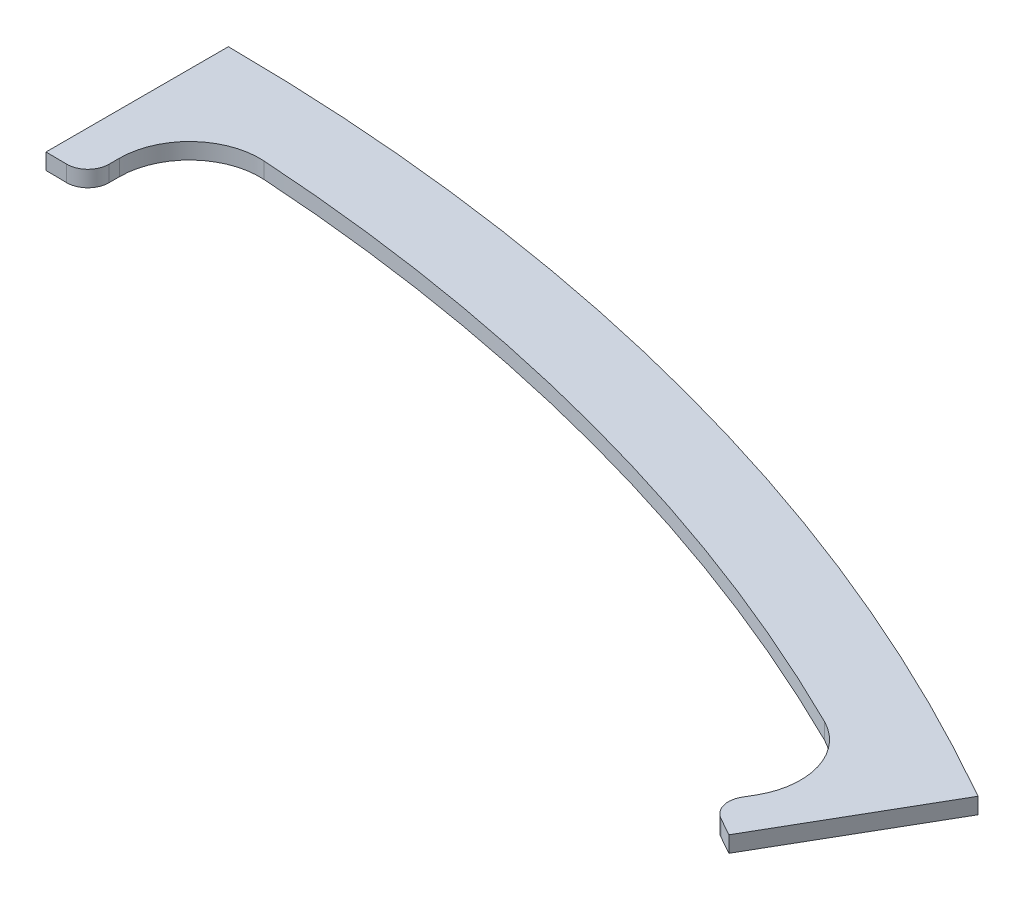
SolidWorks part; units mm, degrees
ref_plane "Front Plane" through (0, 0, 0) normal (0, 0, 1) x (1, 0, 0)
ref_plane "Top Plane" through (0, 0, 0) normal (0, 1, 0) x (1, 0, 0)
ref_plane "Right Plane" through (0, 0, 0) normal (1, 0, 0) x (0, 0, -1)
sketch "Sketch1" plane through (0, 0, 0) normal (0, 1, 0) x (1, 0, 0)
  line L0 (0, 0) -> (0, 297.5) construction
  line L1 (0, 0) -> (148.75, 257.6426) construction
  line L2 (204.8954, 357.8892) -> (-50.4142, -84.3199) construction
  line L3 (1.5, 359.3331) -> (1.5, -61.2496) construction
  line L4 (1.5, 297.4962) -> (1.5, 271.4962)
  line L5 (147.4491, 258.3893) -> (134.4491, 235.8726)
  circle A0 centre (0, 0) radius 297.5 construction
  arc A1 (1.5, 297.4962) -> (147.4491, 258.3893) centre (0, 0) cw
  arc A3 (1.5, 271.4962) -> (134.4491, 235.8726) centre (0, 0) cw
  dimension "D1" = 595
  dimension "D5" = 26
  dimension "D2" = 30
  dimension "D3" = 1.5
  dimension "D4" = 1.5
extrude "Boss-Extrude1" add sketch "Sketch1" along normal blind 2.29
sketch "Sketch3" plane through (0, 2.29, 0) normal (0, 1, 0) x (1, 0, 0)
  line L0 (7.5, 271.3968) -> (129.2032, 238.7865)
  line L3 (7.5, 297.4962) -> (7.5, 271.4962)
  line L4 (7.5, 286.4022) -> (7.5, 271.3968)
  line L8 (129.2529, 238.8726) -> (142.2529, 261.3893)
  line L9 (129.2032, 238.7865) -> (136.7059, 251.7816)
  arc A0 (134.4491, 235.8726) -> (1.5, 271.4962) centre (0, 0) ccw construction
  arc A1 (134.4491, 235.8726) -> (1.5, 271.4962) centre (0, 0) ccw construction
  arc A3 (141.8772, 248.9042) -> (1.5829, 286.496) centre (0, 0) ccw
  arc A4 (136.7059, 251.7816) -> (7.5, 286.4022) centre (0, 0) ccw
  dimension "D1" = 15
  dimension "D2" = 6
  dimension "D3" = 6
extrude "Cut-Extrude1" cut sketch "Sketch3" against normal blind 3
fillet "Fillet1" radius 10 2 edges at (7.5, 1.145, -286.4022) (136.7059, 1.145, -251.7816)
fillet "Fillet2" radius 3 2 edges at (129.2032, 1.145, -238.7865) (7.5, 1.145, -271.3968)
sketch "Sketch5" plane through (1.5, 0, 0) normal (-1, 0, 0) x (0, 0, 1)
  line L1 (-299.7439, -7.0286) -> (-265.7049, -7.0286)
  line L2 (-299.7439, -7.0286) -> (-299.7439, 9.6829)
  line L3 (-299.7439, 9.6829) -> (-265.7049, 9.6829)
  line L4 (-265.7049, -7.0286) -> (-265.7049, 9.6829)
extrude "Cut-Extrude3" [suppressed] cut sketch "Sketch5" against normal blind 10
sketch "Sketch6" plane through (-1.299, 0, -0.75) normal (0.866, 0, 0.5) x (0.5, 0, -0.866)
  line L5 (303.6394, 7.1081) -> (267.2822, 7.1081)
  line L6 (303.6394, 7.1081) -> (303.6394, -5.0551)
  line L7 (303.6394, -5.0551) -> (267.2822, -5.0551)
  line L8 (267.2822, 7.1081) -> (267.2822, -5.0551)
extrude "Cut-Extrude4" [suppressed] cut sketch "Sketch6" against normal blind 10
